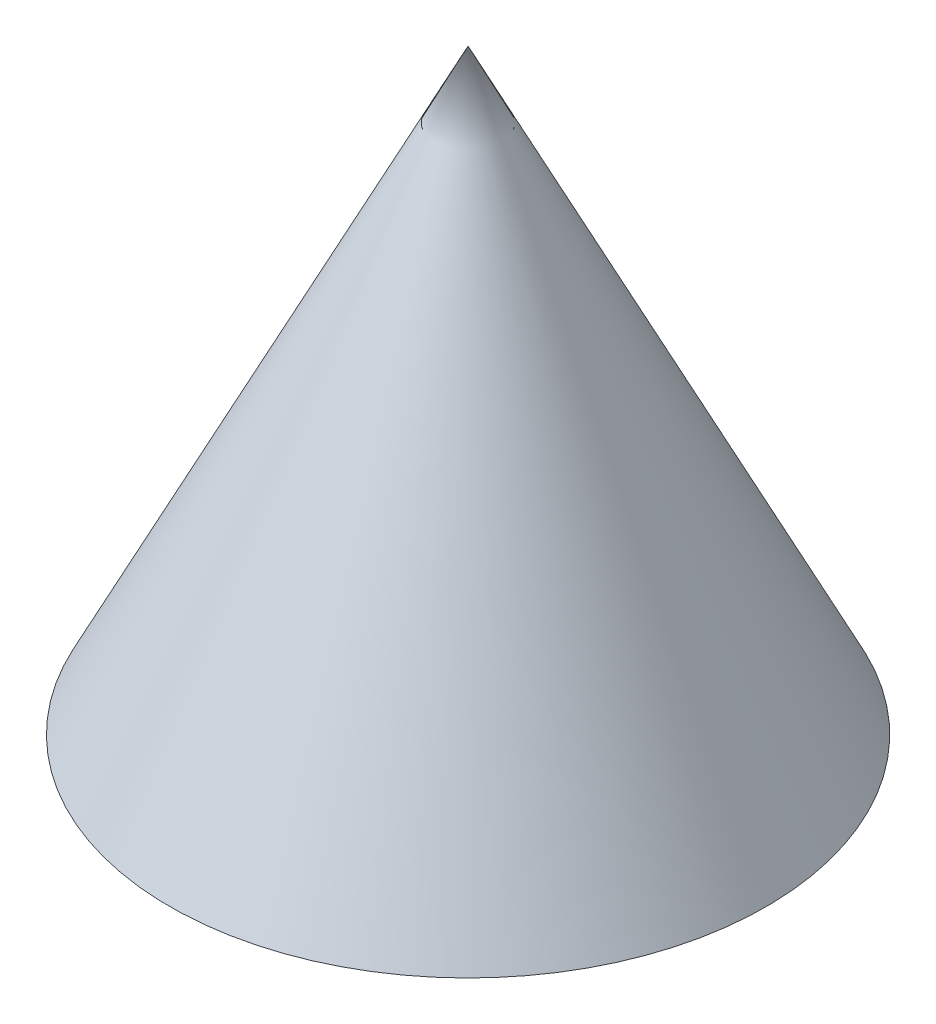
SolidWorks part; units mm, degrees
material "ABS"
ref_plane "Front Plane" through (0, 0, 0) normal (0, 0, 1) x (1, 0, 0)
ref_plane "Top Plane" through (0, 0, 0) normal (0, 1, 0) x (1, 0, 0)
ref_plane "Right Plane" through (0, 0, 0) normal (1, 0, 0) x (0, 0, -1)
sketch "Sketch1" plane through (0, 0, 0) normal (0, 0, 1) x (1, 0, 0)
  line L0 (0, 0) -> (0, 50)
  line L1 (0, 50) -> (25, 0)
  line L2 (25, 0) -> (0, 0)
  dimension "D1" = 50
  dimension "D2" = 25
revolve "Revolve1" add sketch "Sketch1" angle 360 about L0
sketch3d "URDF Reference"
  line L0 (0, 0, 0) -> (10, 0, 0) construction
  line L1 (0, 0, 0) -> (0, 0, -10) construction
  point P0 (0, 0, 0)
  point P1 (0, 0, 0)
